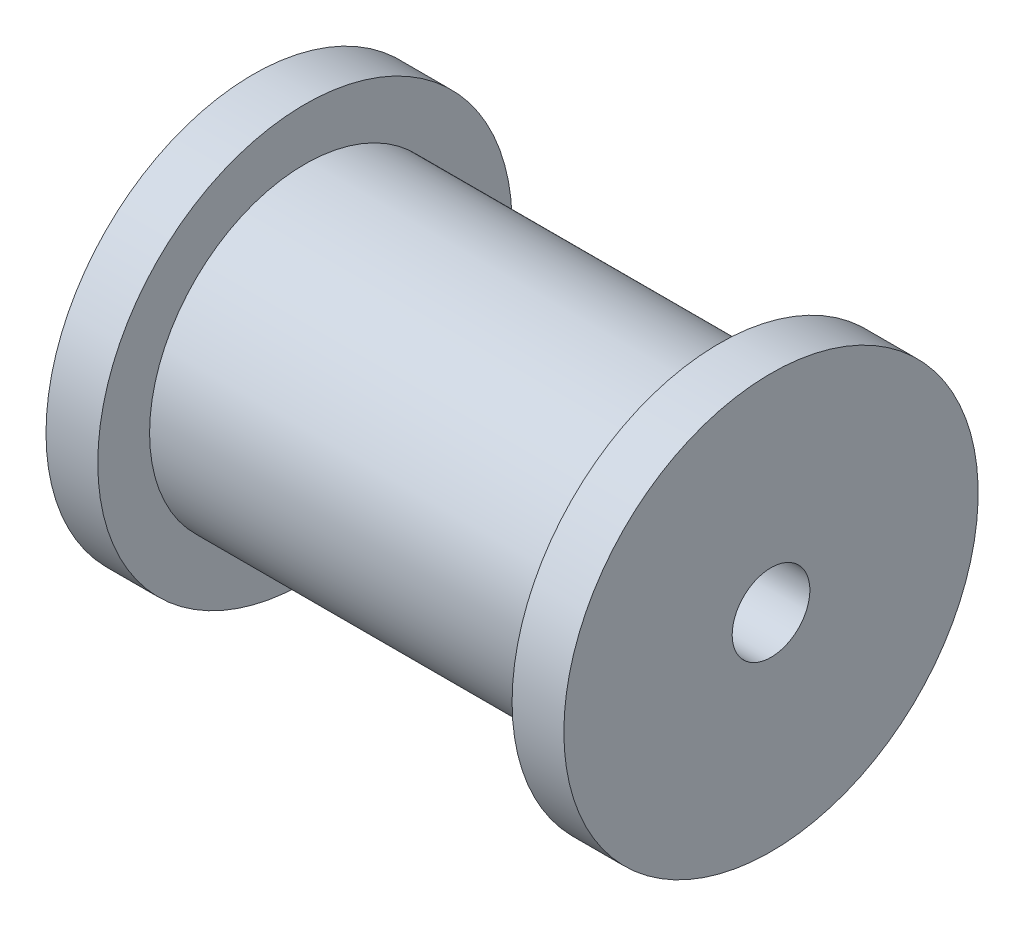
SolidWorks part; units mm, degrees
material "ABS PC"
ref_plane "Front Plane" through (0, 0, 0) normal (0, 0, 1) x (1, 0, 0)
ref_plane "Top Plane" through (0, 0, 0) normal (0, 1, 0) x (1, 0, 0)
ref_plane "Right Plane" through (0, 0, 0) normal (1, 0, 0) x (0, 0, -1)
sketch "Sketch1" plane through (0, 0, 0) normal (1, 0, 0) x (0, 0, -1)
  circle A0 centre (0, 0) radius 25.4
  dimension "D1" = 50.8
extrude "Boss-Extrude1" add sketch "Sketch1" along normal blind 6.35
sketch "Sketch2" plane through (6.35, 0, 0) normal (1, 0, 0) x (0, 0, -1)
  circle A0 centre (0, 0) radius 19.05
  dimension "D1" = 38.1
extrude "Boss-Extrude2" add sketch "Sketch2" along normal blind 50.8
sketch "Sketch3" plane through (57.15, 0, 0) normal (1, 0, 0) x (0, 0, -1)
  circle A1 centre (0, 0) radius 25.4
  dimension "D1" = 50.8
extrude "Boss-Extrude3" add sketch "Sketch3" along normal blind 6.35
sketch "Sketch4" plane through (63.5, 0, 0) normal (1, 0, 0) x (0, 0, -1)
  circle A0 centre (0, 0) radius 4.7625
  dimension "D1" = 9.525
extrude "Cut-Extrude1" cut sketch "Sketch4" against normal through all
move or copy body "Body-Move/Copy1" bodies to move or copy 106
